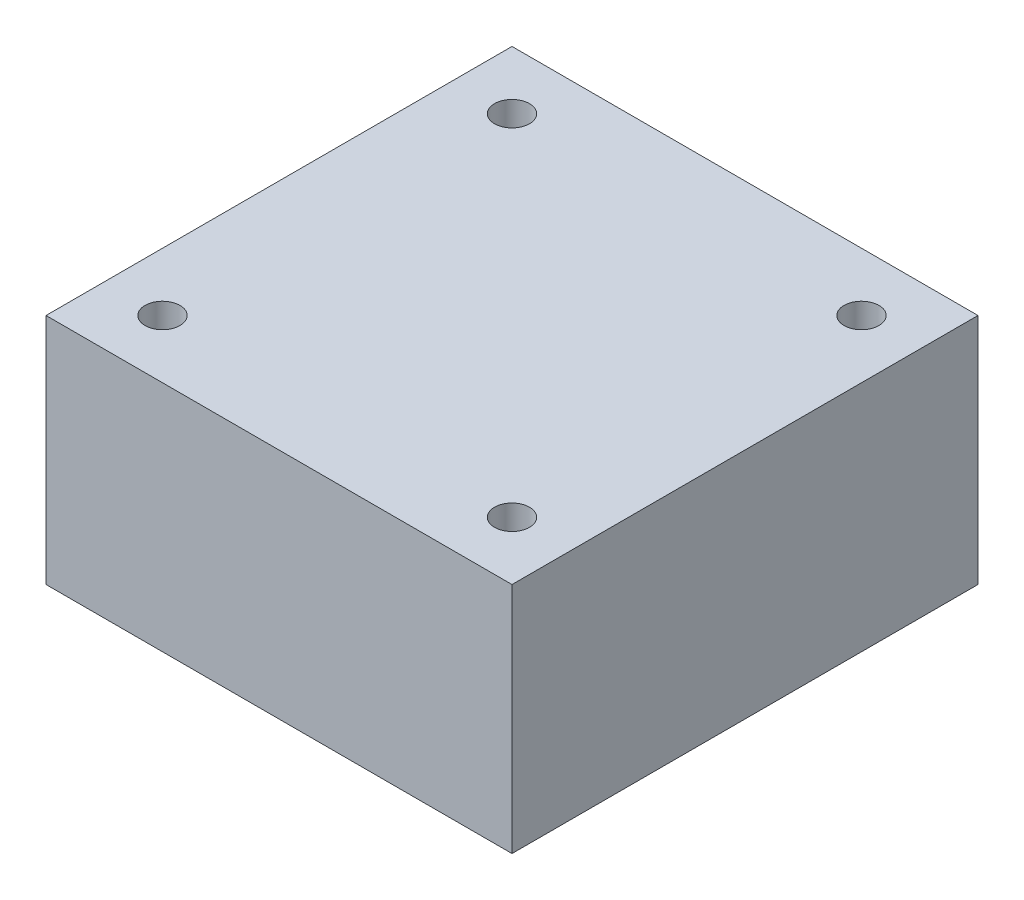
SolidWorks part; units mm, degrees
ref_plane "Front Plane" through (0, 0, 0) normal (0, 0, 1) x (1, 0, 0)
ref_plane "Top Plane" through (0, 0, 0) normal (0, 1, 0) x (1, 0, 0)
ref_plane "Right Plane" through (0, 0, 0) normal (1, 0, 0) x (0, 0, -1)
sketch "Sketch1" plane through (0, 0, 0) normal (0, 1, 0) x (1, 0, 0)
  line L1 (20, -20) -> (-20, -20)
  line L2 (20, -20) -> (20, 20)
  line L3 (20, 20) -> (-20, 20)
  line L4 (-20, -20) -> (-20, 20)
  line L5 (20, -20) -> (-20, 20) construction
  line L6 (20, 20) -> (-20, -20) construction
  line L7 (15, -15) -> (-15, -15)
  line L8 (15, -15) -> (15, 15)
  line L9 (15, 15) -> (-15, 15)
  line L10 (-15, -15) -> (-15, 15)
  line L11 (15, -15) -> (-15, 15) construction
  line L12 (15, 15) -> (-15, -15) construction
  circle A0 centre (-15, 15) radius 1.5
  circle A1 centre (15, 15) radius 1.5
  circle A2 centre (15, -15) radius 1.5
  circle A3 centre (-15, -15) radius 1.5
  point P0 (0, 0)
  point P6 (0, 0)
  point P15 (0, 0)
  point P17 (-15.4203, -15.4203)
  point P18 (0, 0)
  dimension "D5" = 3
  dimension "D6" = 3
  dimension "D7" = 3
  dimension "D8" = 3
  dimension "D1" = 40
  dimension "D2" = 40
  dimension "D3" = 30
  dimension "D4" = 30
extrude "Boss-Extrude1" add sketch "Sketch1" along normal blind 20 contours L4 L1 L2 L3 A3 L10 A0 L9 A1 L8 A2 L7 | A3 L7 A2 L8 A1 L9 A0 L10
